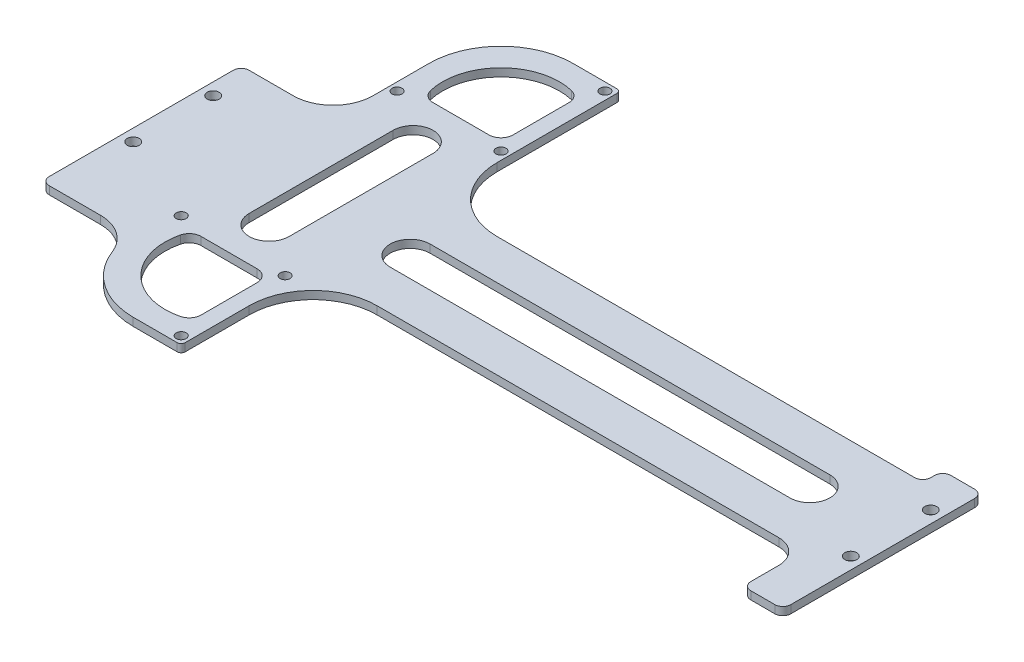
SolidWorks part; units mm, degrees
material "Thornel Mat VMA"
ref_plane "前视基准面" through (0, 0, 0) normal (0, 0, 1) x (1, 0, 0)
ref_plane "上视基准面" through (0, 0, 0) normal (0, 1, 0) x (1, 0, 0)
ref_plane "右视基准面" through (0, 0, 0) normal (1, 0, 0) x (0, 0, -1)
sketch "草图1" plane through (0, 0, 0) normal (0, 1, 0) x (1, 0, 0)
  line L0 (-16.1257, 0) -> (26.9285, 0) construction
  line L1 (0, 20.9555) -> (0, -23.7495) construction
  line L3 (-15, 55) -> (15, 55)
  line L4 (-15, 55) -> (-15, -55)
  line L5 (-15, -55) -> (15, -55)
  line L6 (15, 55) -> (15, -55)
  line L7 (0, -55) -> (0, 55) construction
  line L8 (-15, 0) -> (15, 0) construction
  circle A0 centre (13, 27) radius 1.25
  circle A1 centre (-13, 27) radius 1.25
  circle A2 centre (-13, -27) radius 1.25
  circle A3 centre (13, -27) radius 1.25
  circle A4 centre (13, 53) radius 1.25
  circle A5 centre (13, -53) radius 1.25
  point P13 (0, 0)
  dimension "D1" = 2.5
  dimension "D2" = 26
  dimension "D3" = 54
  dimension "D5" = 2.5
  dimension "D6" = 26
  dimension "D7" = 13
  dimension "D4" = 30
  dimension "D8" = 110
extrude "凸台-拉伸1" add sketch "草图1" along normal blind 2
fillet "圆角1" radius 1 2 edges at (15, 1, 55) (15, 1, -55)
fillet "圆角2" radius 18 2 edges at (-15, 1, 55) (-15, 1, -55)
sketch "草图2" plane through (0, 2, 0) normal (0, 1, 0) x (1, 0, 0)
  line L0 (-15, -37) -> (-38, -37)
  line L1 (-15, 37) -> (-15, -37) construction
  line L2 (-38, -37) -> (-38, 13)
  line L3 (-38, 13) -> (-15, 13)
  line L4 (-15, 13) -> (-15, -37)
  line L5 (-38, -12) -> (-15, -12) construction
  line L6 (-26.5, 13) -> (-26.5, -37) construction
  line L7 (15, 0) -> (-15, 0) construction
  line L8 (15, -54) -> (15, 54) construction
  line L9 (0, 0) -> (0, 55) construction
  line L10 (14, 55) -> (3, 55) construction
  dimension "D1" = 23
  dimension "D2" = 50
  dimension "D3" = 12
extrude "凸台-拉伸2" add sketch "草图2" against normal blind 2
sketch "草图3" plane through (0, 2, 0) normal (0, 1, 0) x (1, 0, 0)
  line L0 (0, 0) -> (189.859, 0) construction
  line L1 (15, 8) -> (147.5, 8)
  line L2 (15, -54) -> (15, 54) construction
  line L3 (147.5, 8) -> (147.5, -22)
  line L4 (147.5, -22) -> (15, -22)
  line L5 (15, 8) -> (15, -22)
  dimension "D1" = 132.5
  dimension "D2" = 22
  dimension "D3" = 8
extrude "凸台-拉伸3" add sketch "草图3" against normal blind 2 contours L1 L3 L4 L5
fillet "圆角3" radius 16 2 edges at (15, 1, -8) (15, 1, 22)
sketch "草图4" plane through (0, 0, 0) normal (0, -1, 0) x (1, 0, 0)
  line L0 (147.5, -13) -> (147.5, 37)
  line L1 (147.5, 37) -> (137.5, 37)
  line L2 (137.5, 37) -> (137.5, -13)
  line L3 (137.5, -13) -> (147.5, -13)
  line L4 (-38, 37) -> (147.5, 37) construction
  line L5 (-38, -13) -> (147.5, -13) construction
  dimension "D1" = 10
extrude "凸台-拉伸4" add sketch "草图4" against normal blind 2
fillet "圆角5" radius 6 1 edges at (137.5, 1, 22)
fillet "圆角6" radius 2 1 edges at (137.5, 1, -8)
fillet "圆角7" radius 2 6 edges at (-38, 1, -13) (-38, 1, 37) (147.5, 1, -13) (147.5, 1, 37) (137.5, 1, 37) (137.5, 1, -13)
sketch "草图5" plane through (0, 0, 0) normal (0, -1, 0) x (1, 0, 0)
  line L0 (13, 53) -> (13, 27) construction
  line L1 (13, 27) -> (-13, 27) construction
  line L2 (-13, 27) -> (13, 53) construction
  line L3 (-8.1716, 29) -> (11, 29)
  line L4 (11, 29) -> (11, 48.1716)
  line L6 (-13, 27) -> (-13, -27) construction
  line L7 (-13, 0) -> (47.516, 0) construction
  line L8 (-13, -27) -> (13, -53) construction
  line L9 (13, -27) -> (-13, -27) construction
  line L10 (13, -53) -> (13, -27) construction
  line L12 (11, -29) -> (11, -48.1716)
  line L13 (-8.1716, -29) -> (11, -29)
  arc A0 (11, 48.1716) -> (-8.1716, 29) centre (5.2808, 34.7192) ccw
  arc A2 (11, -48.1716) -> (-8.1716, -29) centre (5.2808, -34.7192) cw
  dimension "D2" = 2
  dimension "D3" = 2
extrude "切除-拉伸1" cut sketch "草图5" against normal blind 10
sketch "草图6" plane through (0, 0, 0) normal (0, -1, 0) x (1, 0, 0)
  line L0 (0, 18) -> (0, -18) construction
  line L1 (0, -18) -> (0, 18) construction
  line L2 (-5, -18) -> (-5, 18)
  line L3 (5, -18) -> (5, 18)
  arc A0 (-5, -18) -> (5, -18) centre (0, -18) ccw
  arc A1 (5, 18) -> (-5, 18) centre (0, 18) ccw
  point P0 (0, 0)
  point P4 (0, 0)
  dimension "D1" = 5
  dimension "D2" = 36
extrude "切除-拉伸2" cut sketch "草图6" against normal blind 10
fillet "圆角9" radius 10 2 edges at (-15, 1, -13) (-15, 1, 37)
sketch "草图7" plane through (0, 0, 0) normal (0, -1, 0) x (1, 0, 0)
  line L0 (14.7957, 7) -> (141.6379, 7) construction
  line L1 (131.5, 22) -> (31, 22) construction
  line L2 (31, -8) -> (135.5, -8) construction
  line L3 (24.272, 7) -> (124.272, 7) construction
  line L4 (24.272, 12) -> (124.272, 12)
  line L5 (24.272, 2) -> (124.272, 2)
  arc A0 (24.272, 12) -> (24.272, 2) centre (24.272, 7) ccw
  arc A1 (124.272, 2) -> (124.272, 12) centre (124.272, 7) ccw
  point P8 (74.272, 7)
  dimension "D1" = 5
  dimension "D2" = 100
extrude "切除-拉伸3" cut sketch "草图7" against normal blind 10
fillet "圆角10" radius 3 6 edges at (11, 1, -48.1716) (-8.1716, 1, -29) (11, 1, -29) (11, 1, 48.1716) (-8.1716, 1, 29) (11, 1, 29)
sketch "草图8" plane through (0, 0, 0) normal (0, -1, 0) x (1, 0, 0)
  line L0 (-35, 17) -> (147.5, 17) construction
  line L3 (-38, -11) -> (-38, 35) construction
  line L5 (147.5, -11) -> (147.5, 35) construction
  line L6 (-35, -3) -> (147.5, -3) construction
  line L7 (56.25, 17) -> (56.25, -3) construction
  circle A0 centre (-35, 17) radius 1.5
  circle A4 centre (-35, -3) radius 1.5
  circle A5 centre (144.5, 17) radius 1.5
  circle A6 centre (144.5, -3) radius 1.5
  dimension "D1" = 3
  dimension "D2" = 3
  dimension "D3" = 3
  dimension "D4" = 20
  dimension "D5" = 3
  dimension "D6" = 3
  dimension "D7" = 3
  dimension "D8" = 3
  dimension "D9" = 3
extrude "切除-拉伸4" cut sketch "草图8" against normal blind 10
